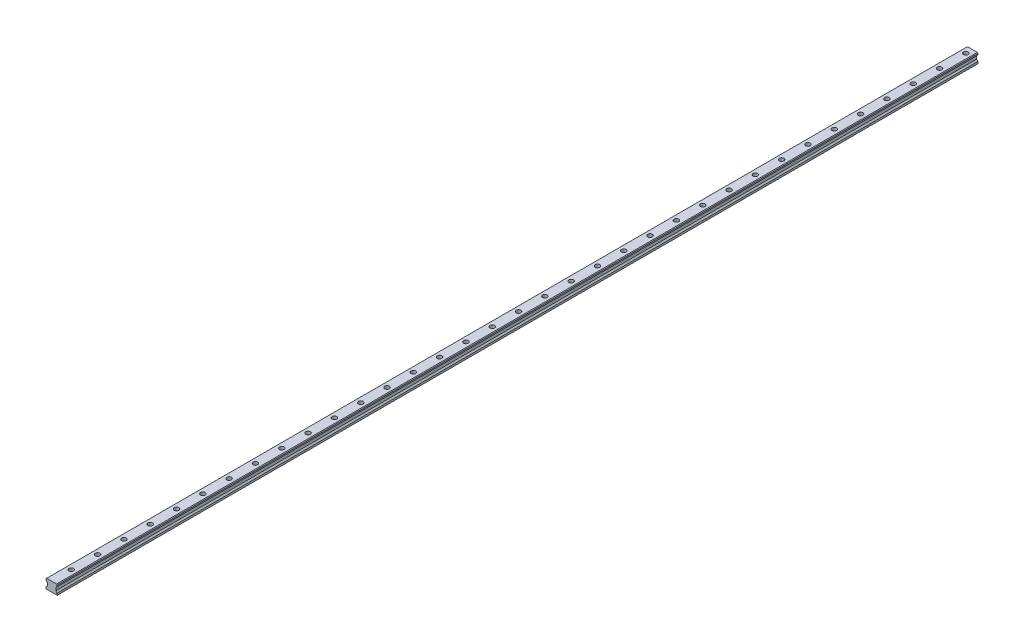
SolidWorks part; units mm, degrees
ref_plane "前视基准面" through (0, 0, 0) normal (0, 0, 1) x (1, 0, 0)
ref_plane "上视基准面" through (0, 0, 0) normal (0, 1, 0) x (1, 0, 0)
ref_plane "右视基准面" through (0, 0, 0) normal (1, 0, 0) x (0, 0, -1)
other "Configuration Table"
sketch "草图1" plane through (0, 0, 0) normal (0, 0, 1) x (1, 0, 0)
  line L0 (0, 45.0632) -> (0, -23.6584) construction
  line L1 (-17, 0) -> (17, 0)
  line L2 (17, 0) -> (17, 6)
  line L3 (17, 6) -> (13, 10)
  line L4 (13, 10) -> (13, 19)
  line L5 (13, 19) -> (17, 23)
  line L6 (17, 23) -> (17, 29)
  line L7 (17, 29) -> (-17, 29)
  line L8 (-17, 23) -> (-17, 29)
  line L9 (-13, 19) -> (-17, 23)
  line L10 (-13, 10) -> (-13, 19)
  line L11 (-17, 6) -> (-13, 10)
  line L12 (-17, 0) -> (-17, 6)
  point P12 (0, 29)
  point P17 (0, 0)
  dimension "D1" = 29
  dimension "D2" = 17
  dimension "D3" = 6
  dimension "D4" = 6
  dimension "D5" = 135
  dimension "D6" = 135
  dimension "D7" = 4
extrude "凸台-拉伸1" add sketch "草图1" along normal blind 2800
chamfer "倒角1" distance 2 angle 45 2 edges at (-17, 29, 1400) (17, 29, 1400)
sketch "草图2" plane through (0, 29, 0) normal (0, 1, 0) x (1, 0, 0)
  line L0 (0, 0) -> (0, -52.6373) construction
  line L1 (15, 0) -> (-15, 0) construction
  circle A0 centre (0, -20) radius 7
  dimension "D1" = 14
  dimension "D2" = 20
extrude "切除-拉伸1" cut sketch "草图2" against normal blind 12
pattern_linear "阵列(线性)1" count 35 spacing 80 along (0, 0, 1) of "切除-拉伸1"
sketch "草图3" plane through (0, 29, 0) normal (0, 1, 0) x (1, 0, 0)
  circle A0 centre (0, -20) radius 4.5
  dimension "D1" = 9
extrude "切除-拉伸2" cut sketch "草图3" against normal blind 40
pattern_linear "阵列(线性)2" count 35 spacing 80 along (0, 0, 1) of "切除-拉伸2"
